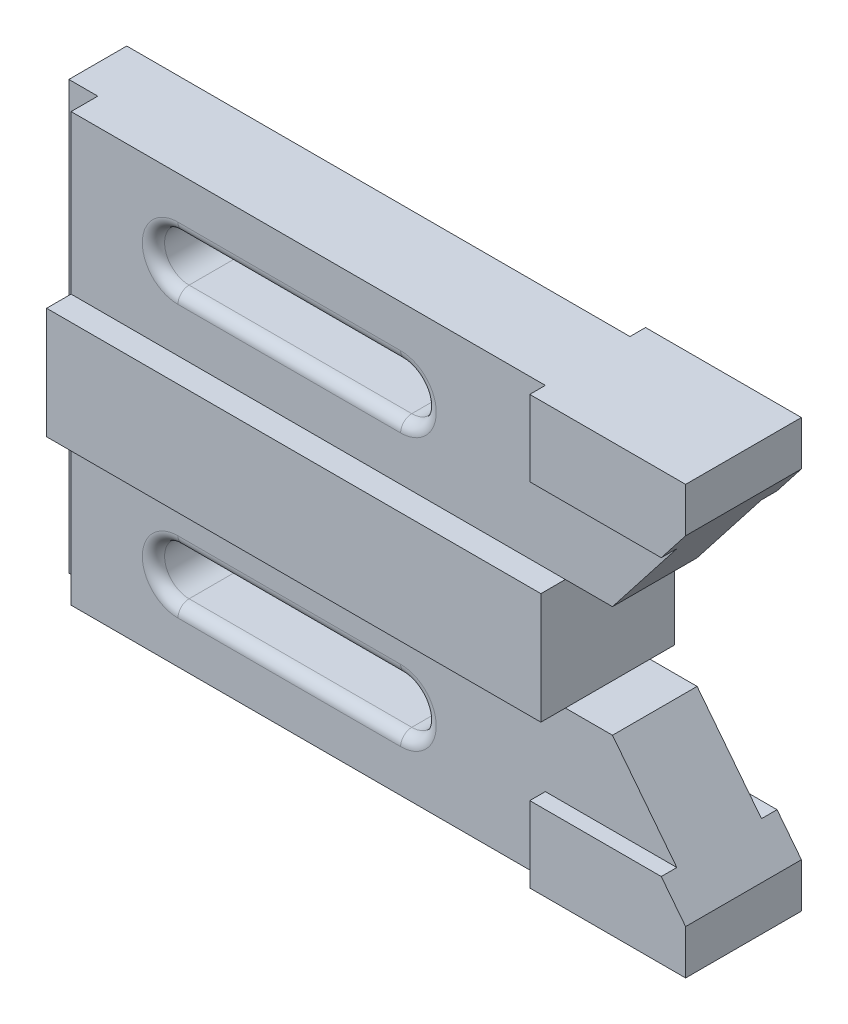
SolidWorks part; units mm, degrees
material "1060 Alloy"
ref_plane "Front Plane" through (0, 0, 0) normal (0, 0, 1) x (1, 0, 0)
ref_plane "Top Plane" through (0, 0, 0) normal (0, 1, 0) x (1, 0, 0)
ref_plane "Right Plane" through (0, 0, 0) normal (1, 0, 0) x (0, 0, -1)
sketch "Sketch1" plane through (0, 0, 0) normal (0, 0, 1) x (1, 0, 0)
  line L0 (0, 0) -> (-148, 0)
  line L1 (-148, 0) -> (-148, 96)
  line L2 (-148, 96) -> (0, 96)
  line L3 (0, 96) -> (0, 86)
  line L5 (-30.5, 60.5) -> (-30.5, 35.5)
  line L6 (-30.5, 35.5) -> (-19.9228, 35.5)
  line L7 (-19.9228, 35.5) -> (0, 10)
  line L8 (0, 10) -> (0, 0)
  line L9 (0, 86) -> (-19.9228, 60.5)
  line L10 (-19.9228, 60.5) -> (-30.5, 60.5)
  line L11 (-117.5, 78.5) -> (-67.5, 78.5) construction
  line L12 (-117.5, 84) -> (-67.5, 84)
  line L13 (-117.5, 73) -> (-67.5, 73)
  line L14 (-117.5, 17.5) -> (-67.5, 17.5) construction
  line L15 (-117.5, 23) -> (-67.5, 23)
  line L16 (-117.5, 12) -> (-67.5, 12)
  arc A0 (-117.5, 84) -> (-117.5, 73) centre (-117.5, 78.5) ccw
  arc A1 (-67.5, 73) -> (-67.5, 84) centre (-67.5, 78.5) ccw
  arc A2 (-117.5, 23) -> (-117.5, 12) centre (-117.5, 17.5) ccw
  arc A3 (-67.5, 12) -> (-67.5, 23) centre (-67.5, 17.5) ccw
  point P12 (-92.5, 78.5)
  point P19 (-92.5, 17.5)
  point P25 (-93.1437, 77.4287)
  point P26 (-93.1437, 23.6227)
  point P27 (0, 0)
  dimension "D12" = 5.5
  dimension "D1" = 148
  dimension "D2" = 96
  dimension "D3" = 10
  dimension "D4" = 52
  dimension "D5" = 35.5
  dimension "D6" = 30.5
  dimension "D7" = 50
  dimension "D8" = 50
  dimension "D9" = 17.5
  dimension "D10" = 30.5
  dimension "D11" = 17.5
extrude "Boss-Extrude1" add sketch "Sketch1" along normal mid plane 19
sketch "Sketch5" plane through (0, 0, 0) normal (0, 0, 1) x (1, 0, 0)
  line L0 (-30.5, 60.5) -> (-148, 60.5)
  line L1 (-148, 96) -> (-148, 0) construction
  line L2 (-30.5, 60.5) -> (-30.5, 35.5)
  line L3 (-30.5, 35.5) -> (-148, 35.5)
  line L4 (-148, 35.5) -> (-148, 60.5)
extrude "Boss-Extrude4" add sketch "Sketch5" along normal mid plane 30
sketch "Sketch6" plane through (0, 0, 0) normal (0, 0, 1) x (1, 0, 0)
  line L0 (-5.469, 79) -> (-35, 79)
  line L1 (-19.9228, 60.5) -> (0, 86) construction
  line L2 (-35, 79) -> (-35, 96)
  line L3 (0, 96) -> (-148, 96) construction
  line L4 (-35, 96) -> (0, 96)
  line L5 (0, 96) -> (0, 86)
  line L6 (0, 86) -> (-5.469, 79)
  line L7 (-5.469, 17) -> (-35, 17)
  line L8 (0, 10) -> (-19.9228, 35.5) construction
  line L9 (-35, 17) -> (-35, 0)
  line L10 (-148, 0) -> (0, 0) construction
  line L11 (-35, 0) -> (0, 0)
  line L12 (0, 0) -> (0, 10)
  line L13 (0, 10) -> (-5.469, 17)
  dimension "D1" = 17
  dimension "D2" = 35
extrude "Boss-Extrude5" add sketch "Sketch6" along normal mid plane 26
sketch "Sketch7" plane through (0, 96, 0) normal (0, 1, 0) x (1, 0, 0)
  line L0 (-141.5, -15) -> (-141.5, -3.5)
  line L1 (-30.5, -15) -> (-148, -15) construction
  line L2 (-141.5, -3.5) -> (-148, -3.5)
  line L3 (-148, -9.5) -> (-148, 9.5) construction
  line L4 (-148, -3.5) -> (-148, -15)
  line L5 (-148, -15) -> (-141.5, -15)
  dimension "D1" = 11.5
  dimension "D2" = 6.5
extrude "Cut-Extrude1" cut sketch "Sketch7" against normal through all
fillet "Fillet1" radius 2.5 16 edges at (-62, 17.5, -9.5) (-92.5, 12, -9.5) (-123, 17.5, -9.5) (-62, 78.5, -9.5) (-92.5, 73, -9.5) (-123, 78.5, -9.5) (-123, 17.5, 9.5) (-92.5, 23, 9.5) (-62, 17.5, 9.5) (-123, 78.5, 9.5) (-92.5, 84, 9.5) (-62, 78.5, 9.5) (-92.5, 23, -9.5) (-92.5, 84, -9.5) (-92.5, 12, 9.5) (-92.5, 73, 9.5)
equation "\"A\" = 148"
equation "\"B\"= 50"
equation "\"C\"= 52"
equation "\"D1@Sketch1\"=\"A\""
equation "\"D4@Sketch1\"=\"C\""
equation "\"D7@Sketch1\"=\"B\""
equation "\"D8@Sketch1\"=\"B\""
equation "\"D11@Sketch1\"=\"D9@Sketch1\""
